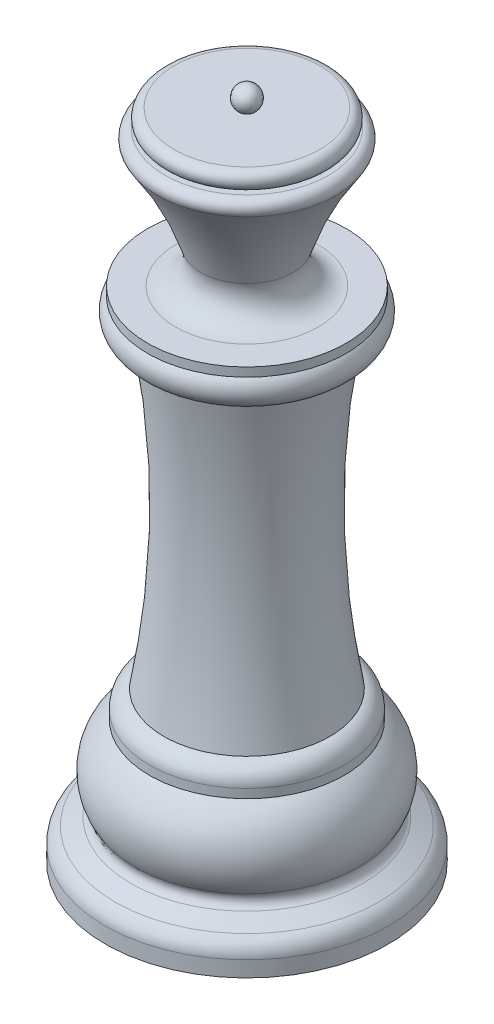
SolidWorks part; units mm, degrees
ref_plane "Front Plane" through (0, 0, 0) normal (0, 0, 1) x (1, 0, 0)
ref_plane "Top Plane" through (0, 0, 0) normal (0, 1, 0) x (1, 0, 0)
ref_plane "Right Plane" through (0, 0, 0) normal (1, 0, 0) x (0, 0, -1)
sketch "Sketch1" plane through (0, 0, 0) normal (0, 0, 1) x (1, 0, 0)
  line L10 (-0.0214, -10) -> (13.9594, -10)
  line L12 (11.992, -5) -> (15.9594, -7)
  line L13 (15.9594, -7) -> (15.9594, -10)
  line L14 (15.9594, -10) -> (13.9594, -10)
  line L15 (10.9594, 3.97) -> (10.9594, 4.97)
  line L16 (11.1823, 46.29) -> (11.1823, 45.29)
  line L17 (-0.0214, 65.9982) -> (-0.0214, -10)
  line L18 (11.1823, 61.7) -> (8.1823, 61.7)
  line L20 (8.1823, 63.7) -> (0.8823, 63.7)
  line L21 (11.1823, 46.29) -> (4.1823, 46.29)
  arc A10 (10.9594, 3.97) -> (11.992, -5) centre (7.5515, -0.9667) cw
  arc A11 (9.3458, 6.97) -> (10.9594, 4.97) centre (8.9598, 5.0076) cw
  arc A12 (11.1823, 45.29) -> (9.1823, 41.97) centre (9.7588, 43.8851) cw
  arc A13 (9.3458, 6.97) -> (9.1823, 41.97) centre (107.7198, 24.9299) cw
  arc A15 (8.1823, 61.7) -> (8.1823, 63.7) centre (8.1823, 62.7) ccw
  arc A17 (11.1823, 61.7) -> (4.1823, 46.29) centre (39.762, 39.4228) ccw
  arc A18 (-0.0214, 65.9982) -> (0.8823, 63.7) centre (-0.0238, 64.6705) cw
  point P15 (0.6823, 60.57)
  dimension "D3" = 8.97
  dimension "D9" = 2
  dimension "D12" = 100
  dimension "D11" = 35
  dimension "D8" = 2
  dimension "D15" = 1
  dimension "D16" = 2
  dimension "D17" = 75.9982
  dimension "D10" = 5.9988
  dimension "D14" = 7.3
  dimension "D1" = 3
  dimension "D2" = 2
  dimension "D4" = 1
  dimension "D5" = 2
  dimension "D6" = 3.32
  dimension "D7" = 1
  dimension "D13" = 15.41
revolve "Revolve1" add sketch "Sketch1" angle 360 about L17
fillet "Fillet1" radius 2 1 edges at (-16.0022, -7, 0)
fillet "Fillet2" radius 1 1 edges at (-12.0347, -5, 0)
fillet "Fillet3" radius 3 1 edges at (-4.225, 46.29, 0)
fillet "Fillet4" radius 1 1 edges at (-11.225, 61.7, 0)
